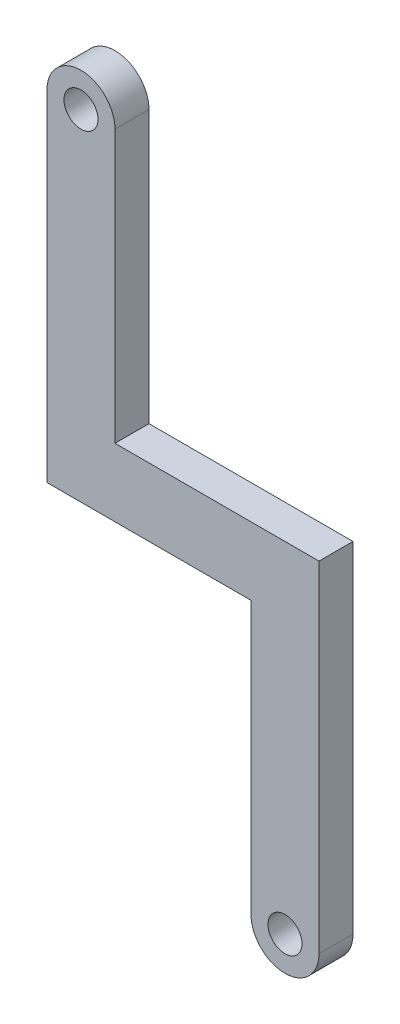
SolidWorks part; units mm, degrees
ref_plane "Front Plane" through (0, 0, 0) normal (0, 0, 1) x (1, 0, 0)
ref_plane "Top Plane" through (0, 0, 0) normal (0, 1, 0) x (1, 0, 0)
ref_plane "Right Plane" through (0, 0, 0) normal (1, 0, 0) x (0, 0, -1)
sketch "Sketch2" plane through (0, 0, 0) normal (0, 0, 1) x (1, 0, 0)
  line L0 (0, 0) -> (0, 25) construction
  line L1 (0, 25) -> (-15, 25) construction
  line L2 (-15, 25) -> (-15, 45) construction
  line L3 (-12.5, 45) -> (-12.5, 25)
  line L4 (2.5, 25) -> (2.5, 0)
  line L5 (-2.5, 20) -> (-2.5, 0)
  line L6 (-17.5, 45) -> (-17.5, 20)
  line L7 (-12.5, 25) -> (2.5, 25)
  line L8 (-17.5, 20) -> (-2.5, 20)
  line L9 (-15, 45) -> (-17.5, 45) construction
  circle A0 centre (0, 0) radius 2.5
  circle A1 centre (0, 0) radius 1.25
  circle A2 centre (-15, 45) radius 1.25
  circle A3 centre (-15, 45) radius 2.5
  point P13 (0, 0)
  point P17 (0, 0)
  dimension "D1" = 5
  dimension "D2" = 2.5
  dimension "D8" = 2.5
  dimension "D3" = 15
  dimension "D4" = 20
  dimension "D5" = 20
  dimension "D6" = 5
  dimension "D7" = 0
  dimension "D9" = 0
extrude "Boss-Extrude2" add sketch "Sketch2" along normal blind 2.5 contours A3 L6 L8 L5 A0 L4 L7 L3 | A3 A2 | A0 A1
